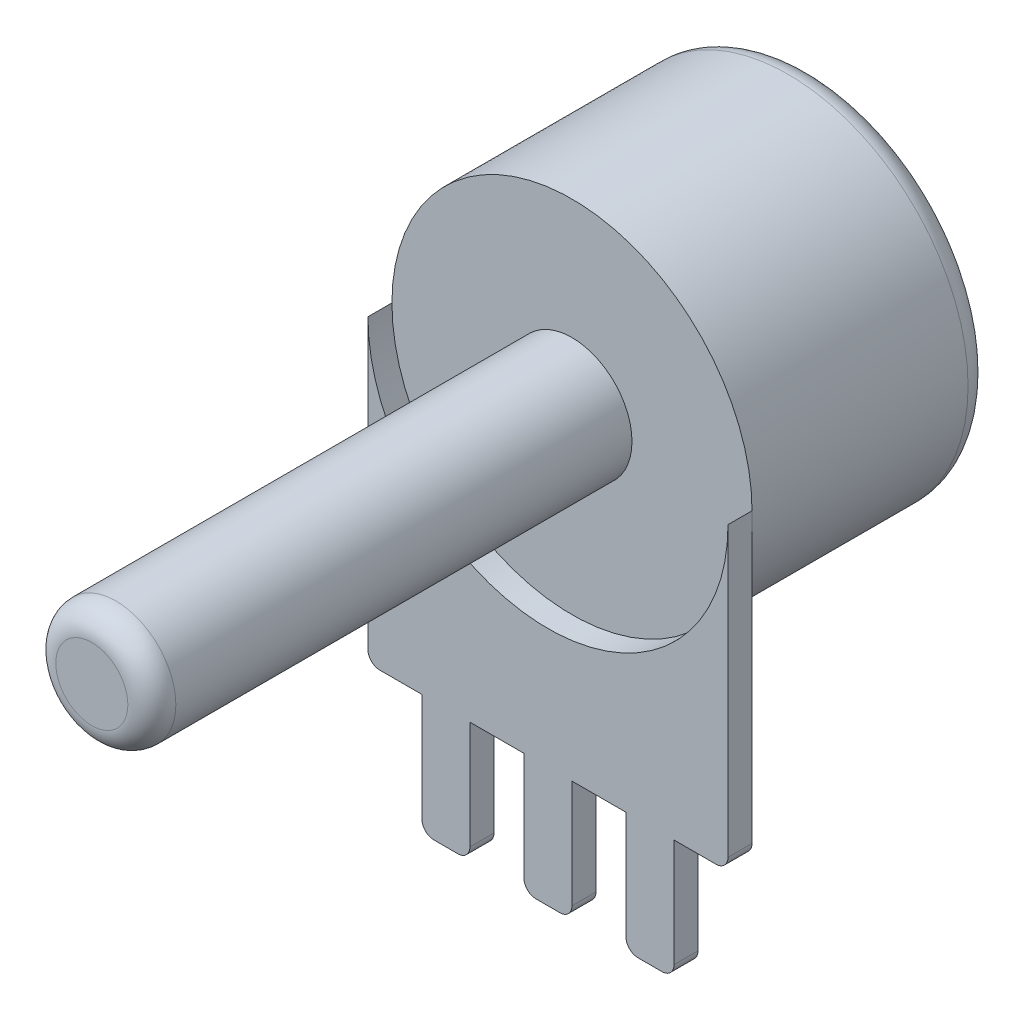
SolidWorks part; units mm, degrees
ref_plane "Ön Düzlem" through (0, 0, 0) normal (0, 0, 1) x (1, 0, 0)
ref_plane "Üst Düzlem" through (0, 0, 0) normal (0, 1, 0) x (1, 0, 0)
ref_plane "Sağ Düzlem" through (0, 0, 0) normal (1, 0, 0) x (0, 0, -1)
sketch "Çizim1" plane through (0, 0, 0) normal (0, 0, 1) x (1, 0, 0)
  circle A0 centre (0, 0) radius 7.5
  dimension "D1" = 15
extrude "Yükseklik-Ekstrüzyon1" add sketch "Çizim1" along normal blind 10
sketch "Çizim2" plane through (0, 0, 10) normal (0, 0, 1) x (1, 0, 0)
  circle A0 centre (0, 0) radius 2.5
  dimension "D1" = 5
extrude "Yükseklik-Ekstrüzyon2" add sketch "Çizim2" along normal blind 20
sketch "Çizim3" plane through (0, 0, 10) normal (0, 0, 1) x (1, 0, 0)
  line L0 (-7.5, 0) -> (-7.5, -7.5)
  line L1 (-7.5, -7.5) -> (-7.5, -12.5)
  line L2 (-7.5, -12.5) -> (-5.25, -12.5)
  line L3 (7.5, -12.5) -> (7.5, -7.5)
  line L4 (7.5, -7.5) -> (7.5, 0)
  line L5 (-5.25, -12.5) -> (-5.25, -17.5)
  line L6 (-5.25, -17.5) -> (-3.25, -17.5)
  line L7 (-3.25, -17.5) -> (-3.25, -12.5)
  line L8 (-3.25, -12.5) -> (-1, -12.5)
  line L9 (-1, -12.5) -> (-1, -17.5)
  line L10 (-1, -17.5) -> (1, -17.5)
  line L11 (1, -17.5) -> (1, -12.5)
  line L12 (3.25, -12.5) -> (3.25, -17.5)
  line L13 (3.25, -17.5) -> (5.25, -17.5)
  line L14 (5.25, -17.5) -> (5.25, -12.5)
  line L15 (1, -12.5) -> (3.25, -12.5)
  line L16 (5.25, -12.5) -> (7.5, -12.5)
  circle A0 centre (0, 0) radius 7.5 construction
  arc A1 (-7.5, 0) -> (7.5, 0) centre (0, 0) ccw
  dimension "D1" = 5
  dimension "D2" = 5
  dimension "D3" = 7.5
  dimension "D4" = 2.25
  dimension "D5" = 2
  dimension "D6" = 5
  dimension "D7" = 3
extrude "Yükseklik-Ekstrüzyon3" add sketch "Çizim3" along normal blind 1 separate body
fillet "Radyus2" radius 1 1 edges at (7.5, 0, 0)
fillet "Radyus3" radius 1 1 edges at (2.5, 0, 30)
fillet "Radyus4" radius 0.5 8 edges at (-7.5, -12.5, 10.5) (7.5, -12.5, 10.5) (5.25, -17.5, 10.5) (3.25, -17.5, 10.5) (1, -17.5, 10.5) (-1, -17.5, 10.5) (-3.25, -17.5, 10.5) (-5.25, -17.5, 10.5)
